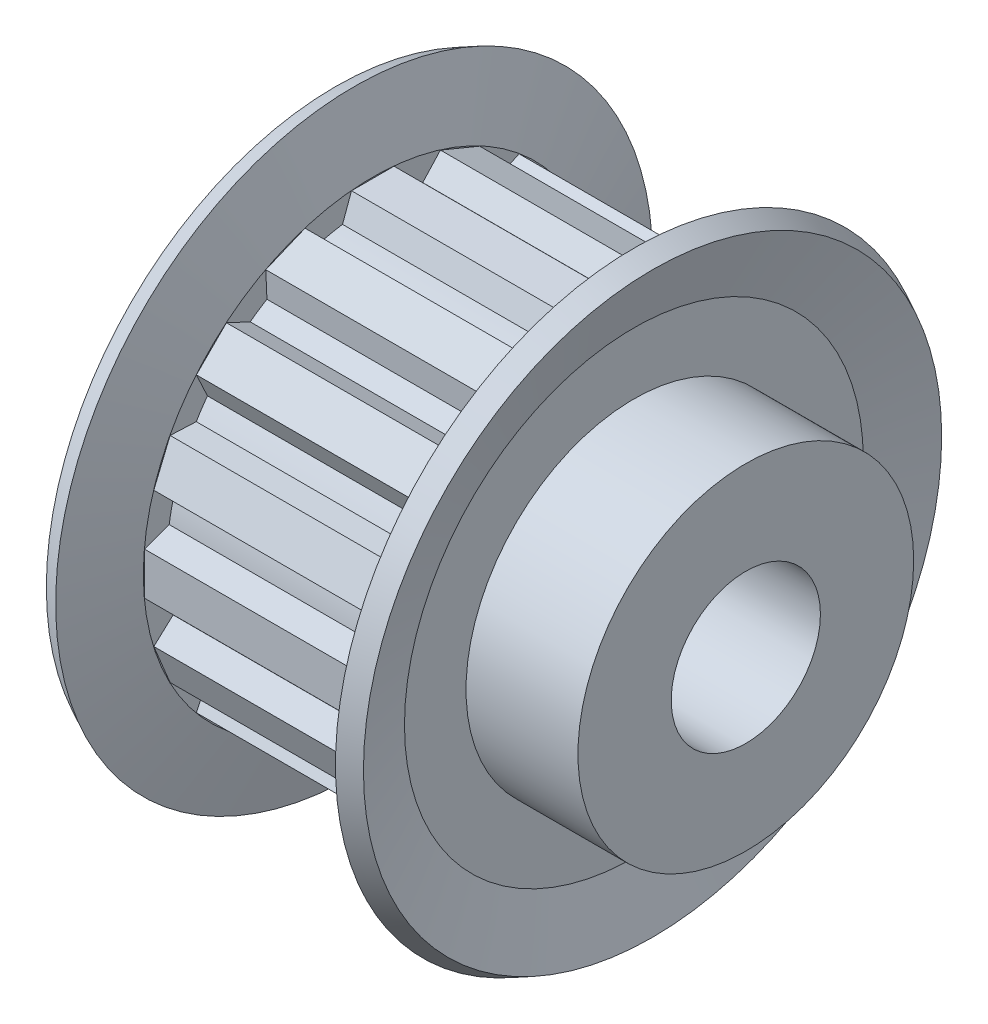
SolidWorks part; units mm, degrees
material "1060 Alloy"
ref_plane "Front Plane" through (0, 0, 0) normal (0, 0, 1) x (1, 0, 0)
ref_plane "Top Plane" through (0, 0, 0) normal (0, 1, 0) x (1, 0, 0)
ref_plane "Right Plane" through (0, 0, 0) normal (1, 0, 0) x (0, 0, -1)
sketch "Sketch1" plane through (0, 0, 0) normal (0, 0, 1) x (1, 0, 0)
  line L0 (-7.5, 12.3) -> (-7.5, 0)
  line L1 (-7.5, 0) -> (7.5, 0)
  line L2 (7.5, 0) -> (7.5, 12.3)
  line L3 (7.5, 12.3) -> (8.5, 15.5)
  line L4 (8.5, 15.5) -> (7.5, 16)
  line L5 (7.5, 16) -> (6.5, 12.3)
  line L6 (6.5, 12.3) -> (6.5, 11.0324)
  line L7 (6.5, 11.0324) -> (-6.5, 11.0324)
  line L8 (-6.5, 11.0324) -> (-6.5, 12.3)
  line L9 (-6.5, 12.3) -> (-7.5, 16)
  line L10 (-7.5, 16) -> (-8.5, 15.5)
  line L11 (-8.5, 15.5) -> (-7.5, 12.3)
  line L12 (-8.5, 0) -> (8.5, 0) construction
revolve "Revolve1" add sketch "Sketch1" angle 360 about L12
sketch "Sketch2" plane through (7.5, 0, 0) normal (1, 0, 0) x (0, 0, -1)
  circle A0 centre (0, 0) radius 9
extrude "Boss-Extrude1" add sketch "Sketch2" along normal blind 6
hole_wizard "Ø6.0 (6) Diameter Hole1" positions "Sketch4" profile "Sketch3" hole size "Ø6.0" standard "ANSI Metric"
sketch "Sketch4" plane through (13.5, 0, 0) normal (1, 0, 0) x (0, 0, -1)
  point P0 (0, 0)
sketch "Sketch3" plane through (13.5, 0, 0) normal (0, 1, 0) x (0, 0, -1)
  line L0 (0, 0) -> (0, 21)
  line L1 (0, 21) -> (4, 21)
  line L2 (4, 21) -> (4, 0)
  line L5 (4, 0) -> (0, 0)
  line L10 (0, 21) -> (-4, 21) construction
  line L11 (0, -6.35) -> (0, 107.95) construction
  dimension "Hole Dia." = 8
  dimension "Hole Depth" = 21
  dimension "Drill Angle" = 180
sketch "Sketch5" plane through (0, 0, 0) normal (0, 0, 1) x (1, 0, 0)
  line L0 (-6.5, -12.2324) -> (6.5, -12.2324)
rib "Rib1" sketch "Sketch5" sketch "Sketch5" thickness 2.2803 extrusion direction parallel to sketch draft on yes draft angle 20 parameters "D1"=2.2803, "D3"=20
ref_plane "Plane1" through (0, 0, 0) normal (0, -1, 0) x (1, 0, 0)
sketch "Sketch6" plane through (0, 0, 0) normal (0, -1, 0) x (1, 0, 0)
  line L0 (-6.5, -12.2324) -> (6.5, -12.2324)
rib "Rib2" sketch "Sketch6" sketch "Sketch6" thickness 2.2803 extrusion direction parallel to sketch draft on yes draft angle 20 parameters "D1"=2.2803, "D3"=20
ref_plane "Plane2" through (0, 0, 0) normal (0, 0, -1) x (-1, 0, 0)
sketch "Sketch7" plane through (0, 0, 0) normal (0, 0, -1) x (-1, 0, 0)
  line L0 (6.5, 12.2324) -> (-6.5, 12.2324)
rib "Rib3" sketch "Sketch7" sketch "Sketch7" thickness 2.2803 extrusion direction parallel to sketch draft on yes draft angle 20 parameters "D1"=2.2803, "D3"=20
sketch "Sketch8" plane through (0, 0, 0) normal (0, 1, 0) x (1, 0, 0)
  line L0 (-6.5, -12.2324) -> (6.5, -12.2324)
rib "Rib4" sketch "Sketch8" sketch "Sketch8" thickness 2.2803 extrusion direction parallel to sketch draft on yes draft angle 20 parameters "D1"=2.2803, "D3"=20
ref_plane "Plane3" through (0, 0, 0) normal (0, 0.7071, -0.7071) x (-1, 0, 0)
sketch "Sketch9" plane through (0, 0, 0) normal (0, 0.7071, -0.7071) x (-1, 0, 0)
  line L0 (6.5, 12.2324) -> (-6.5, 12.2324)
rib "Rib5" sketch "Sketch9" sketch "Sketch9" thickness 2.2803 extrusion direction parallel to sketch draft on yes draft angle 20 parameters "D1"=2.2803, "D3"=20
ref_plane "Plane4" through (0, 0, 0) normal (0, 0.3827, -0.9239) x (-1, 0, 0)
sketch "Sketch10" plane through (0, 0, 0) normal (0, 0.3827, -0.9239) x (-1, 0, 0)
  line L0 (6.5, 12.2324) -> (-6.5, 12.2324)
rib "Rib6" sketch "Sketch10" sketch "Sketch10" thickness 2.2803 extrusion direction parallel to sketch draft on yes draft angle 20 parameters "D1"=2.2803, "D3"=20
ref_plane "Plane5" through (0, 0, 0) normal (0, -0.9239, -0.3827) x (1, 0, 0)
sketch "Sketch11" plane through (0, 0, 0) normal (0, -0.9239, -0.3827) x (1, 0, 0)
  line L0 (-6.5, -12.2324) -> (6.5, -12.2324)
rib "Rib7" sketch "Sketch11" sketch "Sketch11" thickness 2.2803 extrusion direction parallel to sketch draft on yes draft angle 20 parameters "D1"=2.2803, "D3"=20
ref_plane "Plane6" through (0, 0, 0) normal (0, 0.9239, -0.3827) x (-1, 0, 0)
sketch "Sketch12" plane through (0, 0, 0) normal (0, 0.9239, -0.3827) x (-1, 0, 0)
  line L0 (6.5, 12.2324) -> (-6.5, 12.2324)
rib "Rib8" sketch "Sketch12" sketch "Sketch12" thickness 2.2803 extrusion direction parallel to sketch draft on yes draft angle 20 parameters "D1"=2.2803, "D3"=20
ref_plane "Plane7" through (0, 0, 0) normal (0, 0.7071, 0.7071) x (-1, 0, 0)
sketch "Sketch13" plane through (0, 0, 0) normal (0, 0.7071, 0.7071) x (-1, 0, 0)
  line L0 (6.5, 12.2324) -> (-6.5, 12.2324)
rib "Rib9" sketch "Sketch13" sketch "Sketch13" thickness 2.2803 extrusion direction parallel to sketch draft on yes draft angle 20 parameters "D1"=2.2803, "D3"=20
ref_plane "Plane8" through (0, 0, 0) normal (0, -0.7071, -0.7071) x (1, 0, 0)
sketch "Sketch14" plane through (0, 0, 0) normal (0, -0.7071, -0.7071) x (1, 0, 0)
  line L0 (-6.5, -12.2324) -> (6.5, -12.2324)
rib "Rib10" sketch "Sketch14" sketch "Sketch14" thickness 2.2803 extrusion direction parallel to sketch draft on yes draft angle 20 parameters "D1"=2.2803, "D3"=20
ref_plane "Plane9" through (0, 0, 0) normal (0, -0.7071, 0.7071) x (1, 0, 0)
sketch "Sketch15" plane through (0, 0, 0) normal (0, -0.7071, 0.7071) x (1, 0, 0)
  line L0 (-6.5, -12.2324) -> (6.5, -12.2324)
rib "Rib11" sketch "Sketch15" sketch "Sketch15" thickness 2.2803 extrusion direction parallel to sketch draft on yes draft angle 20 parameters "D1"=2.2803, "D3"=20
ref_plane "Plane10" through (0, 0, 0) normal (0, -0.3827, -0.9239) x (1, 0, 0)
sketch "Sketch16" plane through (0, 0, 0) normal (0, -0.3827, -0.9239) x (1, 0, 0)
  line L0 (-6.5, -12.2324) -> (6.5, -12.2324)
rib "Rib12" sketch "Sketch16" sketch "Sketch16" thickness 2.2803 extrusion direction parallel to sketch draft on yes draft angle 20 parameters "D1"=2.2803, "D3"=20
ref_plane "Plane11" through (0, 0, 0) normal (0, -0.3827, 0.9239) x (1, 0, 0)
sketch "Sketch17" plane through (0, 0, 0) normal (0, -0.3827, 0.9239) x (1, 0, 0)
  line L0 (-6.5, -12.2324) -> (6.5, -12.2324)
rib "Rib13" sketch "Sketch17" sketch "Sketch17" thickness 2.2803 extrusion direction parallel to sketch draft on yes draft angle 20 parameters "D1"=2.2803, "D3"=20
ref_plane "Plane12" through (0, 0, 0) normal (0, 0.9239, 0.3827) x (-1, 0, 0)
sketch "Sketch18" plane through (0, 0, 0) normal (0, 0.9239, 0.3827) x (-1, 0, 0)
  line L0 (6.5, 12.2324) -> (-6.5, 12.2324)
rib "Rib14" sketch "Sketch18" sketch "Sketch18" thickness 2.2803 extrusion direction parallel to sketch draft on yes draft angle 20 parameters "D1"=2.2803, "D3"=20
ref_plane "Plane13" through (0, 0, 0) normal (0, -0.9239, 0.3827) x (1, 0, 0)
sketch "Sketch19" plane through (0, 0, 0) normal (0, -0.9239, 0.3827) x (1, 0, 0)
  line L0 (-6.5, -12.2324) -> (6.5, -12.2324)
rib "Rib15" sketch "Sketch19" sketch "Sketch19" thickness 2.2803 extrusion direction parallel to sketch draft on yes draft angle 20 parameters "D1"=2.2803, "D3"=20
ref_plane "Plane14" through (0, 0, 0) normal (0, 0.3827, 0.9239) x (-1, 0, 0)
sketch "Sketch20" plane through (0, 0, 0) normal (0, 0.3827, 0.9239) x (-1, 0, 0)
  line L0 (6.5, 12.2324) -> (-6.5, 12.2324)
rib "Rib16" sketch "Sketch20" sketch "Sketch20" thickness 2.2803 extrusion direction parallel to sketch draft on yes draft angle 20 parameters "D1"=2.2803, "D3"=20
